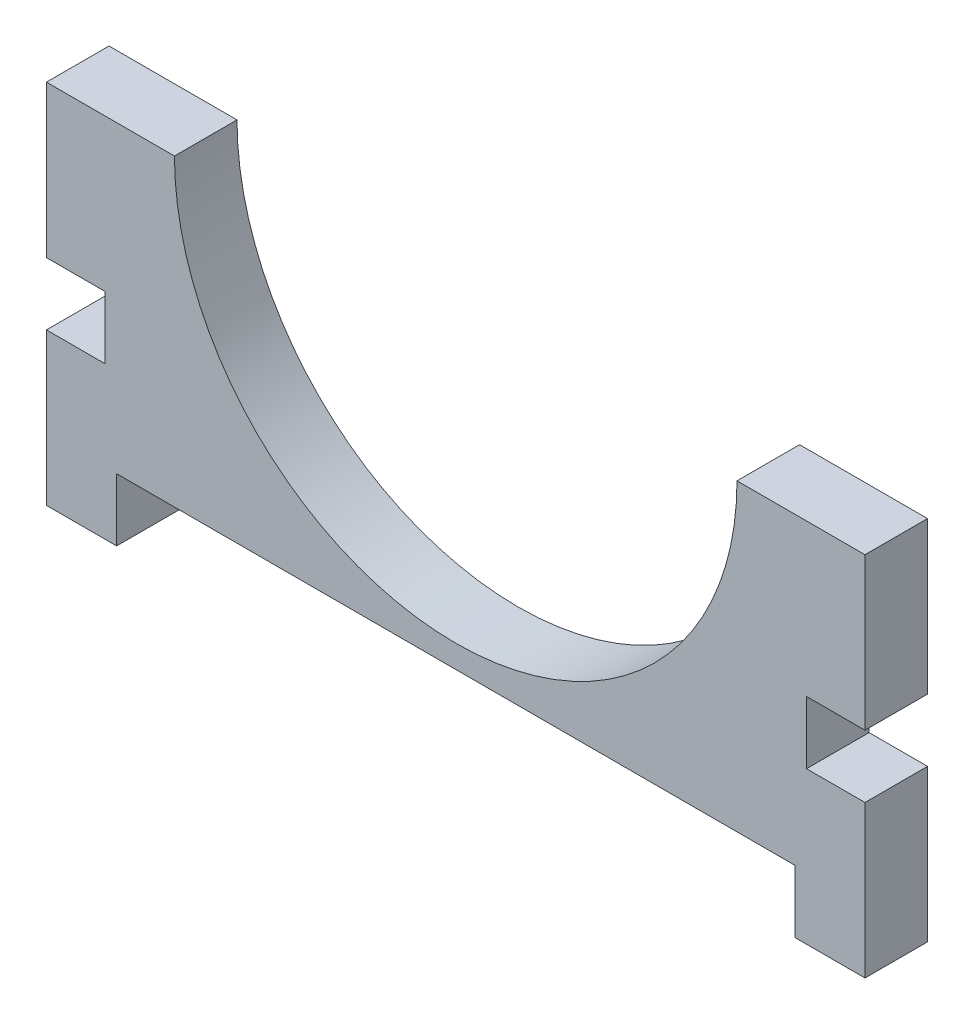
SolidWorks part; units mm, degrees
ref_plane "Front Plane" through (0, 0, 0) normal (0, 0, 1) x (1, 0, 0)
ref_plane "Top Plane" through (0, 0, 0) normal (0, 1, 0) x (1, 0, 0)
ref_plane "Right Plane" through (0, 0, 0) normal (1, 0, 0) x (0, 0, -1)
sketch "Model" plane through (0, 0, 0) normal (0, 0, 1) x (1, 0, 0)
  line L0 (-35, 13) -> (-35, 26)
  line L1 (-29, 0) -> (29, 0)
  line L2 (-35, -5.3175) -> (-35, 7.65)
  line L3 (-35, 26) -> (-24.055, 26)
  line L4 (35, -5.3175) -> (35, 7.65)
  line L5 (-35, 13) -> (-30, 13)
  line L6 (35, -5.3175) -> (35, -5.35)
  line L7 (35, -5.35) -> (29, -5.35)
  line L8 (29, 0) -> (29, -5.35)
  line L9 (0, 0) -> (0, 26) construction
  line L10 (-35, -5.3175) -> (-35, -5.35)
  line L11 (-35, -5.35) -> (-29, -5.35)
  line L12 (-29, 0) -> (-29, -5.35)
  line L13 (-35, 7.65) -> (-30, 7.65)
  line L14 (-30, 13) -> (-30, 7.65)
  line L15 (30, 13) -> (30, 7.65)
  line L16 (35, 7.65) -> (30, 7.65)
  line L17 (35, 13) -> (30, 13)
  line L18 (35, 13) -> (35, 26)
  line L19 (24.055, 26) -> (35, 26)
  line L40 (-35, 26) -> (35, 26) construction
  arc A0 (-24.055, 26) -> (24.055, 26) centre (0, 26) ccw
  dimension "D16" = 24.055
  dimension "D8" = 58
  dimension "D2" = 70
  dimension "D4" = 26
  dimension "D6" = 5.35
  dimension "D9" = 5.35
  dimension "D11" = 5
  dimension "D14" = 13
extrude "Boss-Extrude1" add sketch "Model" along normal blind 5.35
equation "\"mdfthick\"= 5.35"
equation "\"D6@Model\"=\"mdfthick\""
equation "\"D9@Model\"=\"mdfthick\""
equation "\"D1@Boss-Extrude1\"=\"mdfthick\""
